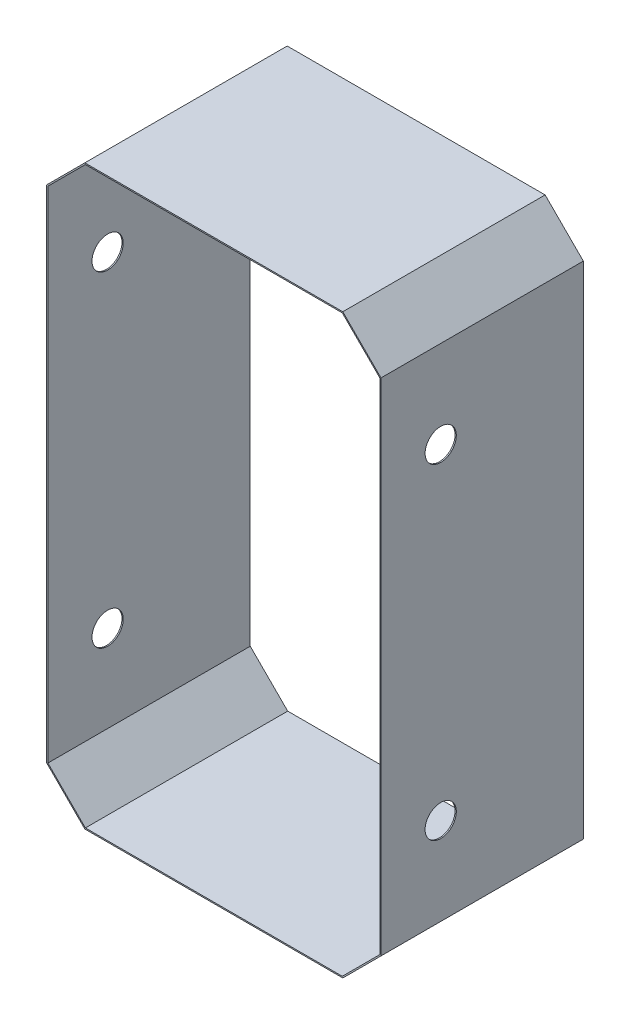
SolidWorks part; units mm, degrees
material "6061-T6 (SS)"
ref_plane "Front Plane" through (0, 0, 0) normal (0, 0, 1) x (1, 0, 0)
ref_plane "Top Plane" through (0, 0, 0) normal (0, 1, 0) x (1, 0, 0)
ref_plane "Right Plane" through (0, 0, 0) normal (1, 0, 0) x (0, 0, -1)
sketch "Sketch1" plane through (0, 0, 0) normal (0, 0, 1) x (1, 0, 0)
  line L16 (-56.7395, 162.3584) -> (-26.7395, 192.3584)
  line L17 (-26.7395, 192.3584) -> (178.9605, 192.3584)
  line L18 (178.9605, 192.3584) -> (208.9605, 162.3584)
  line L19 (208.9605, 162.3584) -> (208.9605, -237.6416)
  line L20 (208.9605, -237.6416) -> (178.9605, -267.6416)
  line L21 (178.9605, -267.6416) -> (-26.7395, -267.6416)
  line L22 (-26.7395, -267.6416) -> (-56.7395, -237.6416)
  line L23 (-56.7395, -237.6416) -> (-56.7395, 162.3584)
  line L24 (-57.7395, 162.7726) -> (-27.1537, 193.3584)
  line L25 (-27.1537, 193.3584) -> (179.3747, 193.3584)
  line L26 (179.3747, 193.3584) -> (209.9605, 162.7726)
  line L27 (209.9605, 162.7726) -> (209.9605, -238.0558)
  line L28 (209.9605, -238.0558) -> (179.3747, -268.6416)
  line L29 (179.3747, -268.6416) -> (-27.1537, -268.6416)
  line L30 (-27.1537, -268.6416) -> (-57.7395, -238.0558)
  line L31 (-57.7395, -238.0558) -> (-57.7395, 162.7726)
extrude "Boss-Extrude1" add sketch "Sketch1" along normal blind 162
sketch "Sketch2" plane through (209.9605, 0, 0) normal (1, 0, 0) x (0, 0, -1)
  line L0 (-162, 92.7726) -> (0, 92.7726) construction
  line L1 (-162, -238.0558) -> (-162, 162.7726) construction
  line L2 (0, -238.0558) -> (0, 162.7726) construction
  line L3 (-114.2, 162.7726) -> (-114.2, -238.0558) construction
  line L4 (-162, 162.7726) -> (0, 162.7726) construction
  line L5 (-162, -238.0558) -> (0, -238.0558) construction
  line L6 (-162, -168.0558) -> (0, -168.0558) construction
  circle A0 centre (-114.2, -168.0558) radius 12.5
  circle A1 centre (-114.2, 92.7726) radius 12.5
  dimension "D4" = 25
  dimension "D5" = 25
  dimension "D1" = 47.8
  dimension "D2" = 70
  dimension "D3" = 70
extrude "Cut-Extrude1" cut sketch "Sketch2" against normal through all
